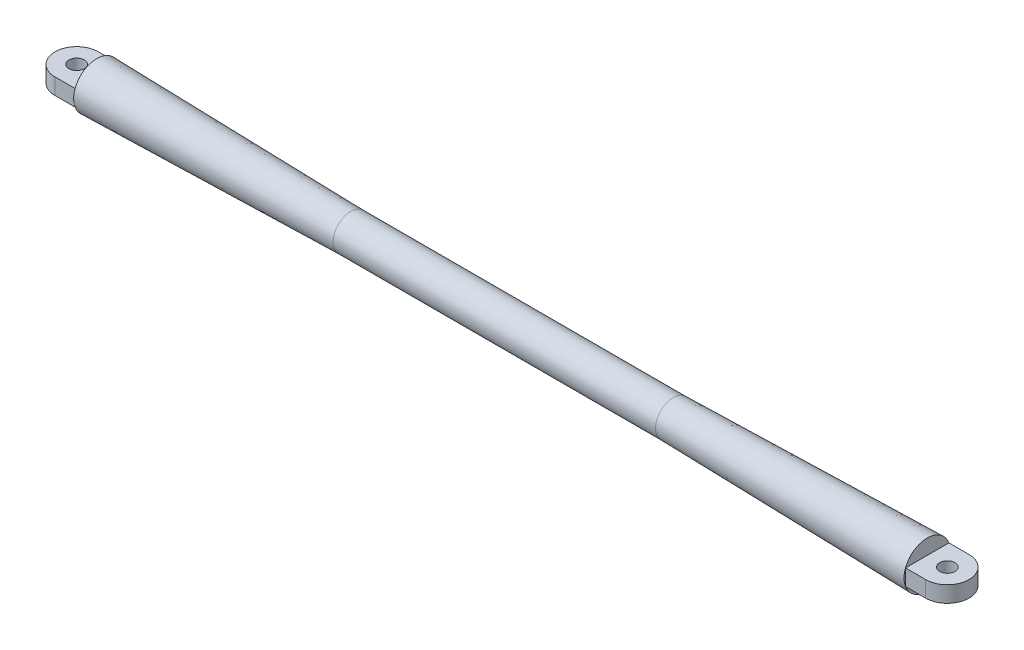
SolidWorks part; units mm, degrees
ref_plane "Front Plane" through (0, 0, 0) normal (0, 0, 1) x (1, 0, 0)
ref_plane "Top Plane" through (0, 0, 0) normal (0, 1, 0) x (1, 0, 0)
ref_plane "Right Plane" through (0, 0, 0) normal (1, 0, 0) x (0, 0, -1)
sketch "Sketch1" plane through (0, 0, 0) normal (0, 1, 0) x (1, 0, 0)
  line L0 (0, 0) -> (575, 0)
  line L1 (575, 0) -> (575, 30)
  line L2 (575, 30) -> (200, 22)
  line L3 (200, 22) -> (0, 22)
  line L4 (0, 22) -> (0, 0)
  dimension "D1" = 200
  dimension "D2" = 22
  dimension "D3" = 575
  dimension "D4" = 30
revolve "Revolve1" add sketch "Sketch1" angle 360 about L0
sketch "Sketch2" plane through (0, 0, 0) normal (0, 0, 1) x (1, 0, 0)
  line L0 (575, 0) -> (590.2909, 0) construction
  line L1 (515, 43.7553) -> (604.6369, 43.7553)
  line L2 (515, 43.7553) -> (515, 10)
  line L3 (515, 10) -> (604.6369, 10)
  line L4 (604.6369, 43.7553) -> (604.6369, 10)
  line L5 (575, -30) -> (575, 30) construction
  line L6 (515, -43.7553) -> (515, -10)
  line L7 (515, -10) -> (604.6369, -10)
  line L8 (604.6369, -43.7553) -> (604.6369, -10)
  line L9 (515, -43.7553) -> (604.6369, -43.7553)
  dimension "D1" = 10
  dimension "D2" = 60
extrude "Cut-Extrude1" cut sketch "Sketch2" against normal through all both and the other way through all
sketch "Sketch3" plane through (0, 10, 0) normal (0, 1, 0) x (1, 0, 0)
  line L0 (515, 26.9228) -> (540, 26.9228)
  line L1 (540, -26.9228) -> (515, -26.9228)
  line L2 (515, 26.9228) -> (515, 52.056)
  line L3 (515, 52.056) -> (621.1374, 52.056)
  line L4 (621.1374, 52.056) -> (621.1374, -26.9228)
  line L5 (621.1374, -26.9228) -> (621.1374, -49.6868)
  line L6 (621.1374, -49.6868) -> (515, -47.4225)
  line L7 (515, -47.4225) -> (515, -26.9228)
  arc A0 (540, 26.9228) -> (540, -26.9228) centre (540, 0) cw
  dimension "D1" = 25
extrude "Cut-Extrude2" cut sketch "Sketch3" against normal through all both and the other way through all
sketch "Sketch4" plane through (0, 10, 0) normal (0, 1, 0) x (1, 0, 0)
  circle A0 centre (540, 0) radius 9.5
  dimension "D1" = 19
extrude "Cut-Extrude3" cut sketch "Sketch4" against normal through all
mirror "Mirror1" about plane through (0, 0, -22) normal (1, 0, 0) of bodies 104
